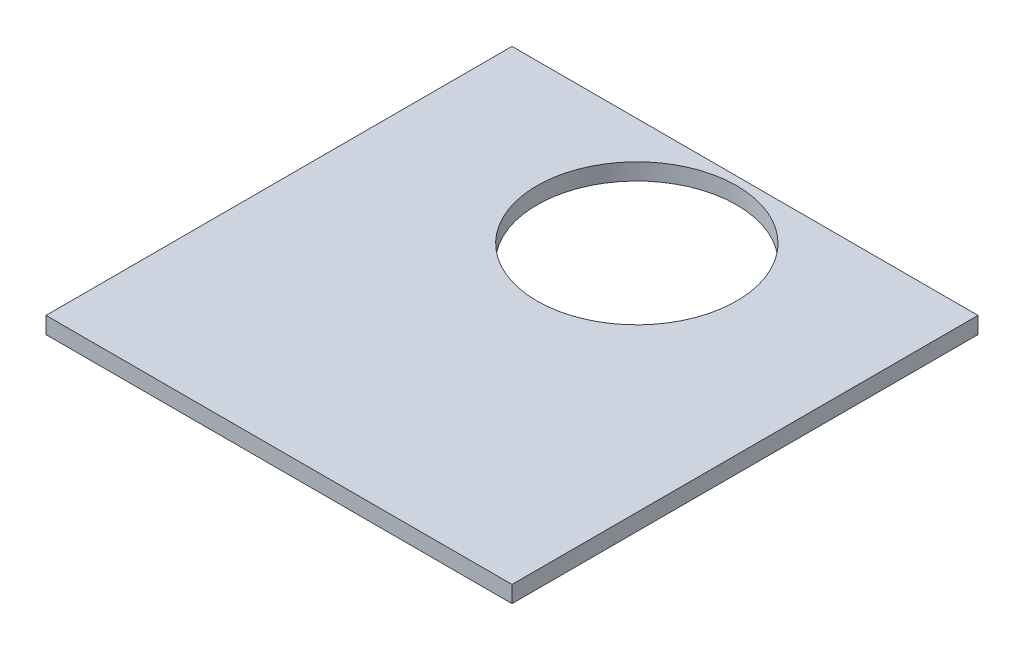
SolidWorks part; units mm, degrees
ref_plane "Front Plane" through (0, 0, 0) normal (0, 0, 1) x (1, 0, 0)
ref_plane "Top Plane" through (0, 0, 0) normal (0, 1, 0) x (1, 0, 0)
ref_plane "Right Plane" through (0, 0, 0) normal (1, 0, 0) x (0, 0, -1)
sketch "Sketch1" plane through (0, 0, 0) normal (0, 1, 0) x (1, 0, 0)
  line L1 (-25.4131, -30.9036) -> (45.7069, -30.9036)
  line L2 (-25.4131, -30.9036) -> (-25.4131, 40.2164)
  line L3 (-25.4131, 40.2164) -> (45.7069, 40.2164)
  line L4 (45.7069, -30.9036) -> (45.7069, 40.2164)
  point P0 (0, 0)
extrude "Boss-Extrude1" add sketch "Sketch1" against normal blind 2.54
sketch "Sketch2" plane through (0, 0, 0) normal (0, 1, 0) x (1, 0, 0)
  circle A0 centre (10.1469, 23.7064) radius 15.24
extrude "Cut-Extrude1" cut sketch "Sketch2" against normal blind 15.748
